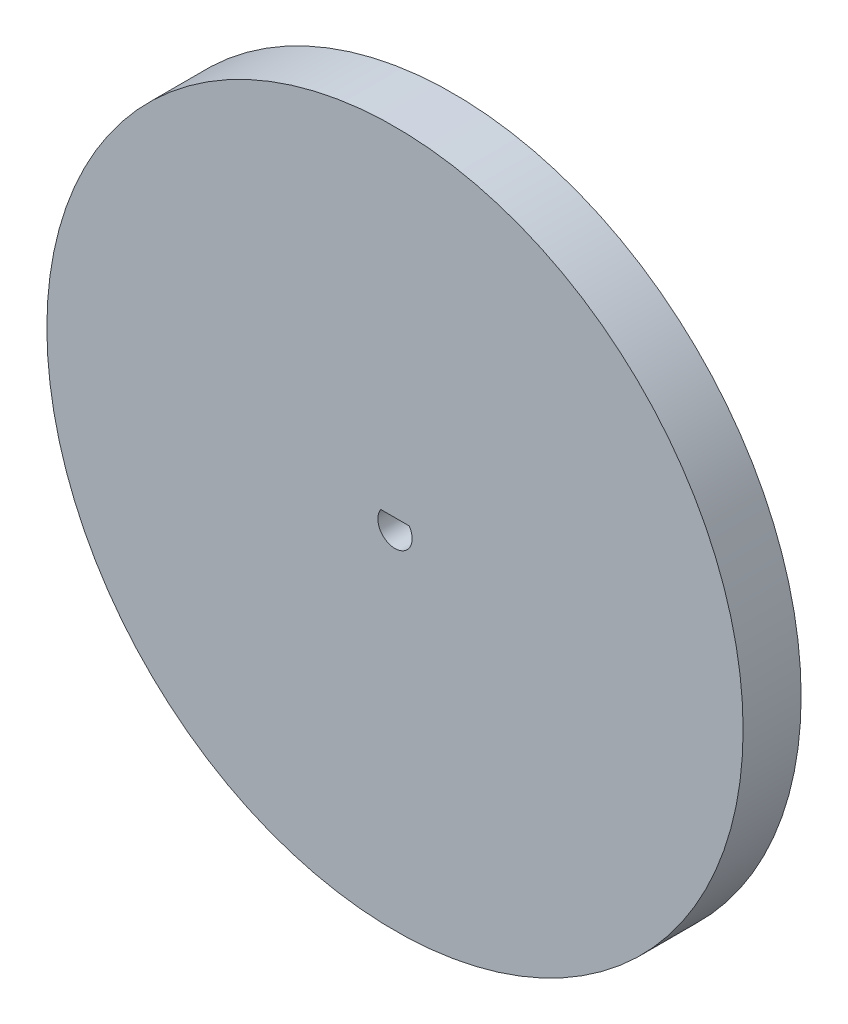
SolidWorks part; units mm, degrees
material "Oak"
ref_plane "Front Plane" through (0, 0, 0) normal (0, 0, 1) x (1, 0, 0)
ref_plane "Top Plane" through (0, 0, 0) normal (0, 1, 0) x (1, 0, 0)
ref_plane "Right Plane" through (0, 0, 0) normal (1, 0, 0) x (0, 0, -1)
sketch "Sketch1" plane through (0, 0, 0) normal (0, 0, 1) x (1, 0, 0)
  circle A0 centre (0, 0) radius 76.2
  dimension "D1" = 152.4
extrude "Boss-Extrude1" add sketch "Sketch1" along normal mid plane 12.7
sketch "Sketch2" plane through (0, 0, 6.35) normal (0, 0, 1) x (1, 0, 0)
  line L0 (-3.1068, 2.1) -> (3.1068, 2.1)
  arc A0 (-3.1068, 2.1) -> (3.1068, 2.1) centre (0, 0) ccw
  point P1 (0, -3.75)
  dimension "D1" = 7.5
  dimension "D2" = 5.85
extrude "Cut-Extrude1" cut sketch "Sketch2" against normal through all
